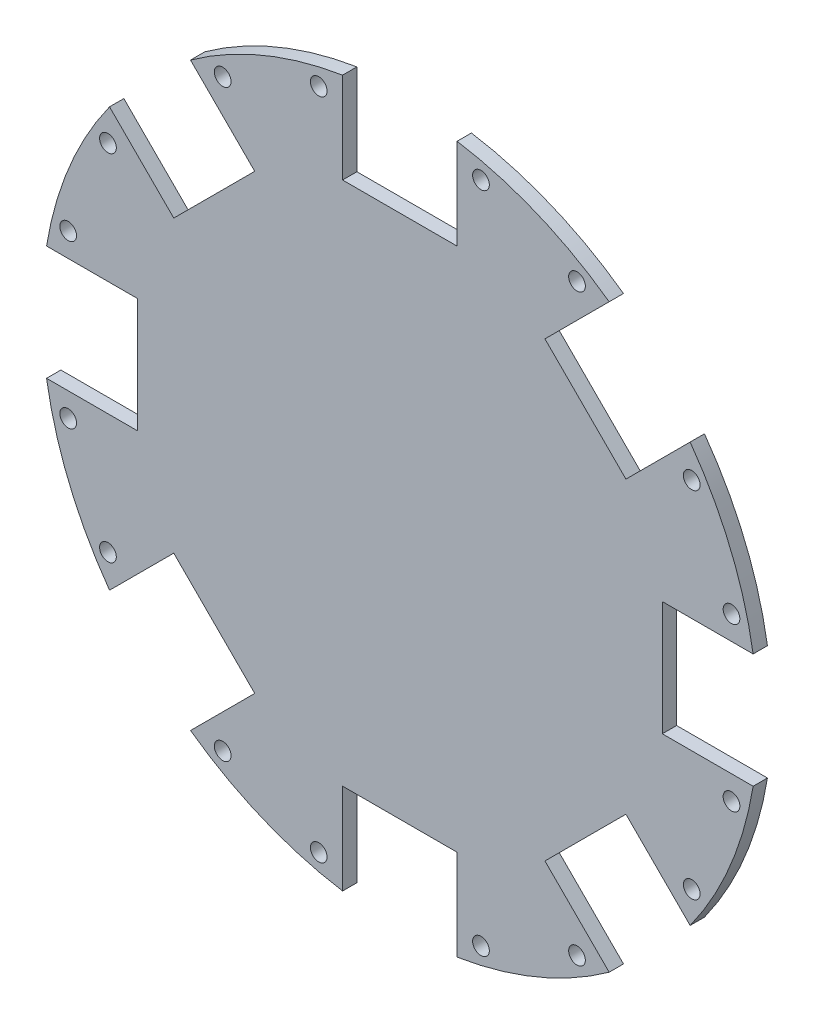
SolidWorks part; units mm, degrees
ref_plane "Front Plane" through (0, 0, 0) normal (0, 0, 1) x (1, 0, 0)
ref_plane "Top Plane" through (0, 0, 0) normal (0, 1, 0) x (1, 0, 0)
ref_plane "Right Plane" through (0, 0, 0) normal (1, 0, 0) x (0, 0, -1)
sketch "Sketch1" plane through (0, 0, 0) normal (0, 0, 1) x (1, 0, 0)
  line L0 (0, 0) -> (0, 75)
  line L1 (-12, 55) -> (12, 55)
  line L2 (-17, 69.5) -> (17, 69.5)
  line L3 (-12, 55) -> (-12, 74.0338)
  line L4 (12, 55) -> (12, 74.0338)
  line L5 (30.4056, 47.3762) -> (43.8645, 60.8351)
  line L6 (30.4056, 47.3762) -> (47.3762, 30.4056)
  line L7 (47.3762, 30.4056) -> (60.8351, 43.8645)
  line L8 (55, 12) -> (74.0338, 12)
  line L9 (55, 12) -> (55, -12)
  line L10 (55, -12) -> (74.0338, -12)
  line L11 (47.3762, -30.4056) -> (60.8351, -43.8645)
  line L12 (47.3762, -30.4056) -> (30.4056, -47.3762)
  line L13 (30.4056, -47.3762) -> (43.8645, -60.8351)
  line L14 (12, -55) -> (12, -74.0338)
  line L15 (12, -55) -> (-12, -55)
  line L16 (-12, -55) -> (-12, -74.0338)
  line L17 (-30.4056, -47.3762) -> (-43.8645, -60.8351)
  line L18 (-30.4056, -47.3762) -> (-47.3762, -30.4056)
  line L19 (-47.3762, -30.4056) -> (-60.8351, -43.8645)
  line L20 (-55, -12) -> (-74.0338, -12)
  line L21 (-55, -12) -> (-55, 12)
  line L22 (-55, 12) -> (-74.0338, 12)
  line L23 (-47.3762, 30.4056) -> (-60.8351, 43.8645)
  line L24 (-47.3762, 30.4056) -> (-30.4056, 47.3762)
  line L25 (-30.4056, 47.3762) -> (-43.8645, 60.8351)
  circle A0 centre (0, 0) radius 75
  circle A1 centre (-17, 69.5) radius 1.75
  circle A2 centre (17, 69.5) radius 1.75
  circle A3 centre (61.1647, 37.1231) radius 1.75
  circle A4 centre (37.1231, 61.1647) radius 1.75
  circle A5 centre (69.5, -17) radius 1.75
  circle A6 centre (69.5, 17) radius 1.75
  circle A7 centre (37.1231, -61.1647) radius 1.75
  circle A8 centre (61.1647, -37.1231) radius 1.75
  circle A9 centre (-17, -69.5) radius 1.75
  circle A10 centre (17, -69.5) radius 1.75
  circle A11 centre (-61.1647, -37.1231) radius 1.75
  circle A12 centre (-37.1231, -61.1647) radius 1.75
  circle A13 centre (-69.5, 17) radius 1.75
  circle A14 centre (-69.5, -17) radius 1.75
  circle A15 centre (-37.1231, 61.1647) radius 1.75
  circle A16 centre (-61.1647, 37.1231) radius 1.75
  point P2 (0, 55)
  point P7 (0, 55)
  point P10 (0, 69.5)
  dimension "D1" = 150
  dimension "D6" = 3.5
  dimension "D2" = 20
  dimension "D3" = 24
  dimension "D4" = 34
  dimension "D5" = 14.5
  dimension "D7" = 0
  dimension "D8" = 8
extrude "Boss-Extrude2" add sketch "Sketch1" along normal blind 3
